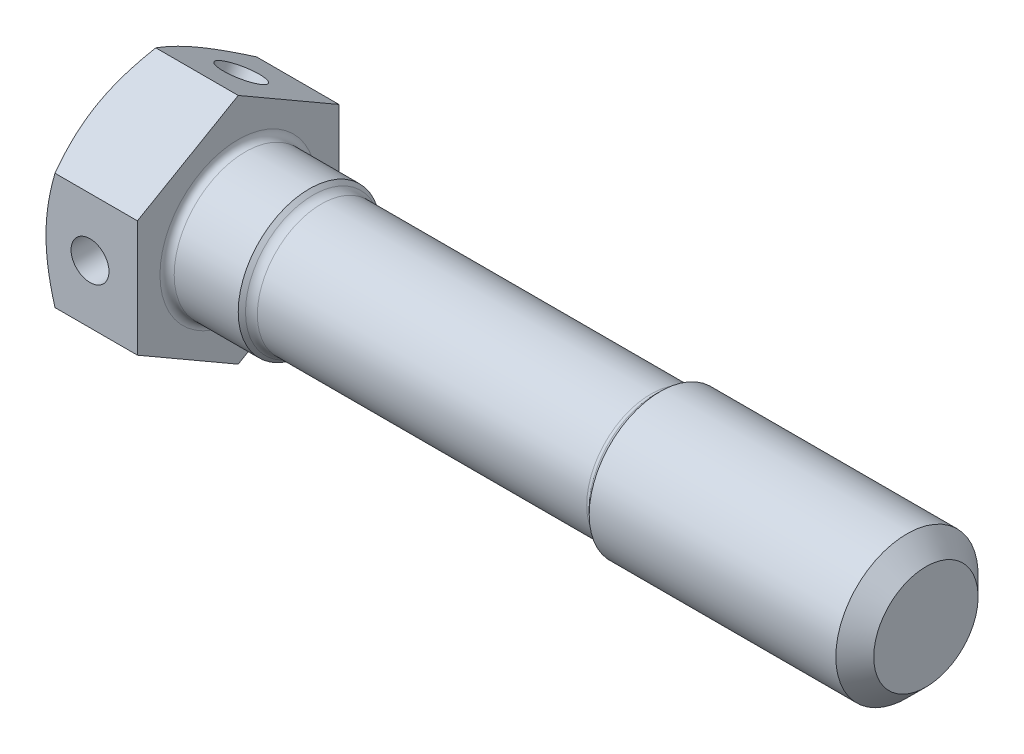
SolidWorks part; units mm, degrees
material "Простая углеродистая сталь"
ref_plane "Спереди" through (0, 0, 0) normal (0, 0, 1) x (1, 0, 0)
ref_plane "Сверху" through (0, 0, 0) normal (0, 1, 0) x (1, 0, 0)
ref_plane "Справа" through (0, 0, 0) normal (1, 0, 0) x (0, 0, -1)
other "Таблицы"
sketch "Эскиз1" plane through (0, 0, 0) normal (0, 0, 1) x (1, 0, 0)
  line L0 (0, 0) -> (41.4975, 0) construction
  line L1 (0, 0) -> (0, 6)
  line L2 (0, 6) -> (6, 6)
  line L3 (6, 6) -> (6.3071, 5.6929)
  line L4 (7.0142, 5.4) -> (34.7929, 5.4)
  line L5 (35.1464, 5.5464) -> (35.6, 6)
  line L6 (35.6, 6) -> (56.4, 6)
  line L7 (58, 4.4) -> (58, 0)
  line L8 (58, 0) -> (0, 0)
  line L9 (56.4, 6) -> (58, 4.4)
  arc A0 (7.0142, 5.4) -> (6.3071, 5.6929) centre (7.0142, 6.4) cw
  arc A1 (35.1464, 5.5464) -> (34.7929, 5.4) centre (34.7929, 5.9) cw
  point P3 (58, 6)
  point P16 (35, 5.4)
  dimension "D10" = 1
  dimension "D11" = 0.5
  dimension "D1" = 12
  dimension "D2" = 10.8
  dimension "D3" = 12
  dimension "D4" = 45
  dimension "D5" = 6
  dimension "D6" = 23
  dimension "D7" = 58
  dimension "D8" = 1.6
  dimension "D9" = 45
revolve "Повернуть1" add sketch "Эскиз1" angle 360 about L0
cosmetic thread "Условное изображение резьбы1" parameters "D2"=10.072
sketch "Эскиз2" plane through (0, 0, 0) normal (-1, 0, 0) x (0, 0, 1)
  line L0 (-8.5, 0) -> (8.5, 0) construction
  line L1 (0, -9.815) -> (0, 9.815) construction
  line L3 (0, -9.815) -> (8.5, -4.9075)
  line L4 (8.5, -4.9075) -> (8.5, 4.9075)
  line L5 (8.5, 4.9075) -> (0, 9.815)
  line L6 (0, 9.815) -> (-8.5, 4.9075)
  line L7 (-8.5, 4.9075) -> (-8.5, -4.9075)
  line L8 (-8.5, -4.9075) -> (0, -9.815)
  circle A0 centre (0, 0) radius 9.815 construction
  point P6 (0, 0)
  dimension "D1" = 17
extrude "Бобышка-Вытянуть1" add sketch "Эскиз2" along normal blind 8
sketch "Эскиз3" plane through (-8, 0, 0) normal (-1, 0, 0) x (0, 0, 1)
  circle A0 centre (0, 0) radius 8
  dimension "D1" = 16
extrude "Вырез-Вытянуть1" cut sketch "Эскиз3" against normal through all draft 60 flip side to cut
fillet "Скругление1" radius 0.6 1 edges at (0, 0, 6)
sketch "Эскиз4" plane through (0, 0, 8.5) normal (0, 0, 1) x (1, 0, 0)
  line L0 (-9.9529, 0) -> (8.4534, 0) construction
  line L1 (-8, 8) -> (-8, -8) construction
  circle A0 centre (-4, 0) radius 1.6
  dimension "D1" = 3.2
  dimension "D2" = 4
extrude "Вырез-Вытянуть2" cut sketch "Эскиз4" against normal through all
sketch "Эскиз5" plane through (0, -7.3612, 4.25) normal (0, -0.866, 0.5) x (1, 0, 0)
  line L0 (-10.0003, 0) -> (5.1327, 0) construction
  line L1 (-8, 8) -> (-8, -8) construction
  circle A0 centre (-4, 0) radius 1.75
  dimension "D1" = 3.5
  dimension "D2" = 4
extrude "Вырез-Вытянуть3" cut sketch "Эскиз5" against normal through all
